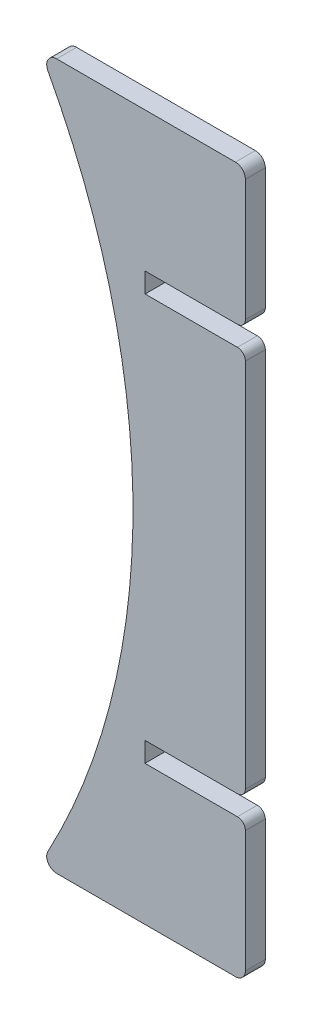
SolidWorks part; units mm, degrees
ref_plane "Plano frontal" through (0, 0, 0) normal (0, 0, 1) x (1, 0, 0)
ref_plane "Plano superior" through (0, 0, 0) normal (0, 1, 0) x (1, 0, 0)
ref_plane "Plano direito" through (0, 0, 0) normal (1, 0, 0) x (0, 0, -1)
sketch "Model" plane through (0, 0, 0) normal (0, 0, 1) x (1, 0, 0)
  line L0 (8.9589, 92.5) -> (-14.205, 92.5)
  line L1 (-14.205, 92.5) -> (-14.205, 87.5)
  line L2 (-14.205, 87.5) -> (8.9589, 87.5)
  line L3 (10.9589, 85.5) -> (10.9589, -7.5)
  line L4 (8.9589, -9.5) -> (-14.2374, -9.5)
  line L5 (-14.2374, -9.5) -> (-14.2374, -14.5)
  line L6 (-14.2374, -14.5) -> (8.9589, -14.5)
  line L7 (10.9589, -16.5) -> (10.9589, -47.0001)
  line L8 (8.4589, -49.5001) -> (-36.3922, -49.5001)
  line L9 (-36.3922, 127.4999) -> (8.4589, 127.4999)
  line L10 (10.9589, 124.9999) -> (10.9589, 94.5)
  arc A0 (10.9589, 85.5) -> (8.9589, 87.5) centre (8.9589, 85.5) ccw
  arc A1 (8.9589, -9.5) -> (10.9589, -7.5) centre (8.9589, -7.5) ccw
  arc A2 (10.9589, -16.5) -> (8.9589, -14.5) centre (8.9589, -16.5) ccw
  arc A3 (8.4589, -49.5001) -> (10.9589, -47.0001) centre (8.4589, -47.0001) ccw
  arc A4 (-38.6049, -45.8365) -> (-36.3922, -49.5001) centre (-36.3922, -47.0001) ccw
  arc A5 (-38.6049, -45.8365) -> (-38.6052, 123.837) centre (-196.3893, 38.9999) ccw
  arc A6 (-36.3922, 127.4999) -> (-38.6052, 123.837) centre (-36.3922, 124.9999) ccw
  arc A7 (10.9589, 124.9999) -> (8.4589, 127.4999) centre (8.4589, 124.9999) ccw
  arc A8 (8.9589, 92.5) -> (10.9589, 94.5) centre (8.9589, 94.5) ccw
extrude "Ressalto-extrusão1" add sketch "Model" along normal blind 5
